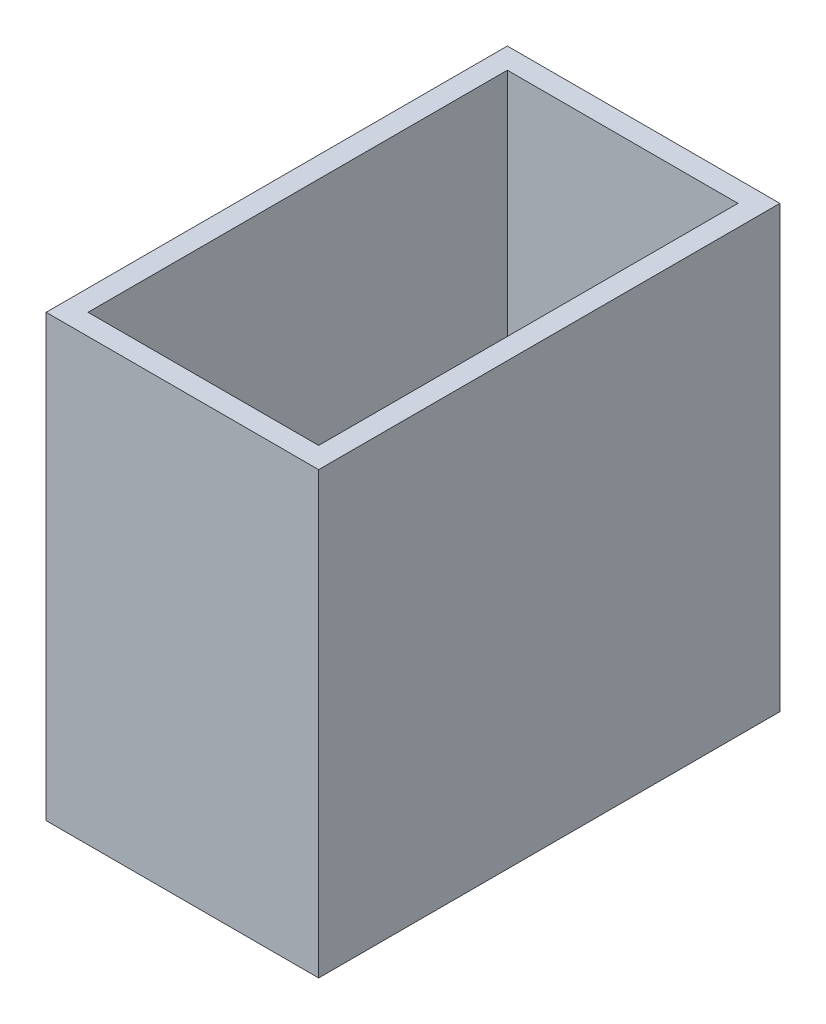
SolidWorks part; units mm, degrees
ref_plane "Alzado" through (0, 0, 0) normal (0, 0, 1) x (1, 0, 0)
ref_plane "Planta" through (0, 0, 0) normal (0, 1, 0) x (1, 0, 0)
ref_plane "Vista lateral" through (0, 0, 0) normal (1, 0, 0) x (0, 0, -1)
sketch "Croquis1" plane through (0, 0, 0) normal (0, 1, 0) x (1, 0, 0)
  line L1 (13, 22) -> (-13, 22)
  line L2 (13, 22) -> (13, -22)
  line L3 (13, -22) -> (-13, -22)
  line L4 (-13, 22) -> (-13, -22)
  line L5 (13, 22) -> (-13, -22) construction
  line L6 (13, -22) -> (-13, 22) construction
  point P0 (0, 0)
  dimension "D1" = 44
  dimension "D2" = 26
extrude "Saliente-Extruir1" add sketch "Croquis1" along normal blind 2
sketch "Croquis2" plane through (0, 2, 0) normal (0, 1, 0) x (1, 0, 0)
  line L1 (11, 20) -> (-11, 20)
  line L2 (11, 20) -> (11, -20)
  line L3 (11, -20) -> (-11, -20)
  line L4 (-11, 20) -> (-11, -20)
  line L5 (11, 20) -> (-11, -20) construction
  line L6 (11, -20) -> (-11, 20) construction
  line L7 (13, -22) -> (-13, -22)
  line L8 (13, -22) -> (13, 22)
  line L9 (13, 22) -> (-13, 22)
  line L10 (-13, -22) -> (-13, 22)
  line L11 (13, -22) -> (-13, 22) construction
  line L12 (13, 22) -> (-13, -22) construction
  point P0 (0, 0)
  point P5 (0, 0)
  dimension "D1" = 40
extrude "Saliente-Extruir2" add sketch "Croquis2" along normal blind 40
